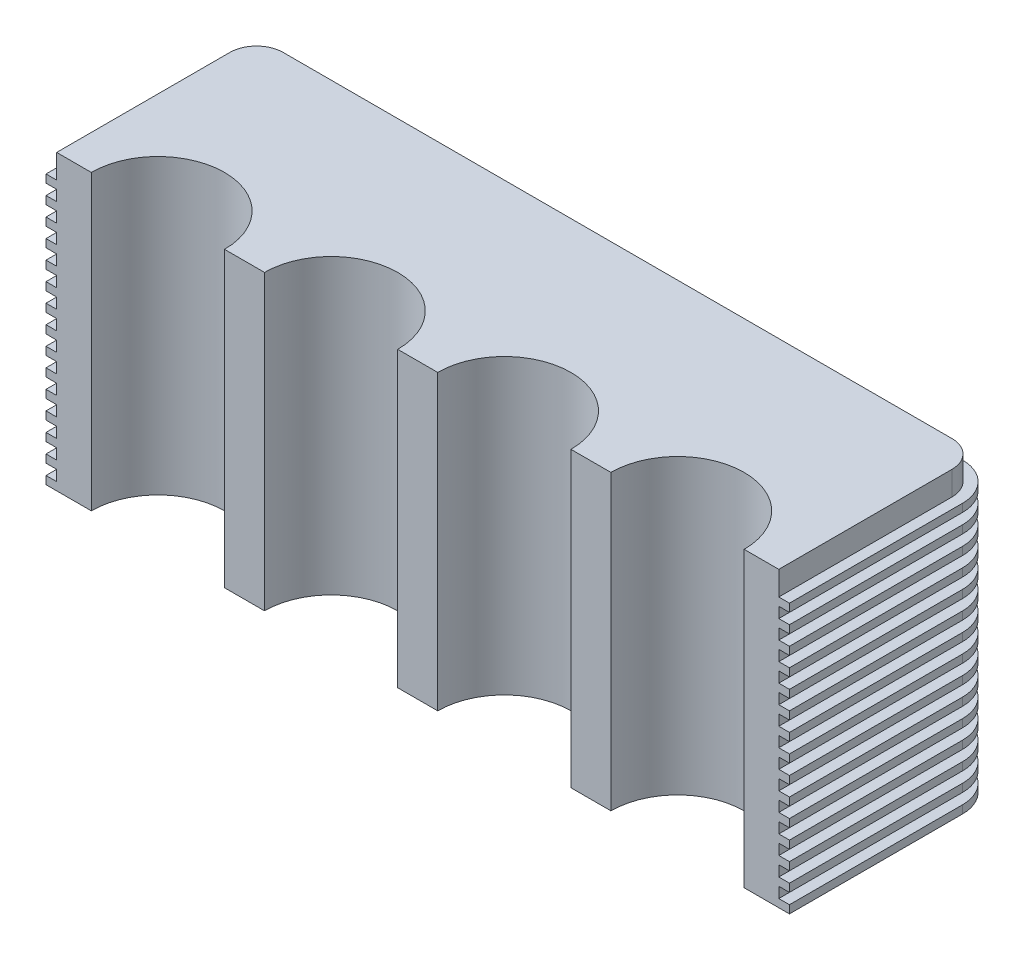
SolidWorks part; units mm, degrees
ref_plane "Front Plane" through (0, 0, 0) normal (0, 0, 1) x (1, 0, 0)
ref_plane "Top Plane" through (0, 0, 0) normal (0, 1, 0) x (1, 0, 0)
ref_plane "Right Plane" through (0, 0, 0) normal (1, 0, 0) x (0, 0, -1)
sketch "Sketch1" plane through (0, 0, 0) normal (0, 1, 0) x (1, 0, 0)
  line L0 (0, 0) -> (271, 75) construction
  line L1 (0, 0) -> (13, 0)
  line L2 (0, 0) -> (0, 65)
  line L3 (10, 75) -> (261, 75)
  line L4 (271, 0) -> (271, 65)
  line L5 (271, 0) -> (0, 75) construction
  line L6 (135.5, 0) -> (135.5, 75) construction
  line L7 (193, 0) -> (208, 0)
  line L8 (258, 0) -> (271, 0)
  line L9 (63, 0) -> (78, 0)
  line L10 (128, 0) -> (143, 0)
  arc A0 (0, 65) -> (10, 75) centre (10, 65) cw
  arc A1 (261, 75) -> (271, 65) centre (261, 65) cw
  arc A2 (258, 0) -> (208, 0) centre (233, 0) ccw
  arc A4 (193, 0) -> (143, 0) centre (168, 0) ccw
  arc A5 (13, 0) -> (63, 0) centre (38, 0) cw
  arc A6 (78, 0) -> (128, 0) centre (103, 0) cw
  dimension "D1" = 10
  dimension "D4" = 50
  dimension "D6" = 50
  dimension "D2" = 271
  dimension "D3" = 65
  dimension "D5" = 38
  dimension "D7" = 15
extrude "Boss-Extrude1" add sketch "Sketch1" along normal blind 110
sketch "Sketch2" plane through (0, 0, 0) normal (0, 1, 0) x (1, 0, 0)
  line L0 (275, 0) -> (275, 65)
  line L1 (261, 79) -> (10, 79)
  line L2 (-4, 65) -> (-4, 0)
  line L3 (271, 0) -> (275, 0)
  line L4 (0, 0) -> (-4, 0)
  line L8 (0, 65) -> (0, 0)
  line L9 (261, 75) -> (10, 75)
  line L10 (271, 0) -> (271, 65)
  line L11 (258, 0) -> (271, 0)
  line L12 (193, 0) -> (208, 0)
  line L13 (128, 0) -> (143, 0)
  line L14 (63, 0) -> (78, 0)
  line L15 (0, 0) -> (13, 0)
  line L16 (0, 65) -> (0, 0)
  line L17 (261, 75) -> (10, 75)
  line L18 (271, 0) -> (271, 65)
  arc A0 (275, 65) -> (261, 79) centre (261, 65) ccw
  arc A1 (10, 79) -> (-4, 65) centre (10, 65) ccw
  arc A6 (10, 75) -> (0, 65) centre (10, 65) ccw
  arc A7 (271, 65) -> (261, 75) centre (261, 65) ccw
  arc A8 (258, 0) -> (208, 0) centre (233, 0) ccw
  arc A9 (193, 0) -> (143, 0) centre (168, 0) ccw
  arc A10 (128, 0) -> (78, 0) centre (103, 0) ccw
  arc A11 (63, 0) -> (13, 0) centre (38, 0) ccw
  arc A12 (10, 75) -> (0, 65) centre (10, 65) ccw
  arc A13 (271, 65) -> (261, 75) centre (261, 65) ccw
  dimension "D1" = 0
  dimension "D2" = 4
extrude "Boss-Extrude2" add sketch "Sketch2" along normal blind 3
pattern_linear "LPattern1" count 15 spacing 7 along (0, 1, 0) of "Boss-Extrude2"
